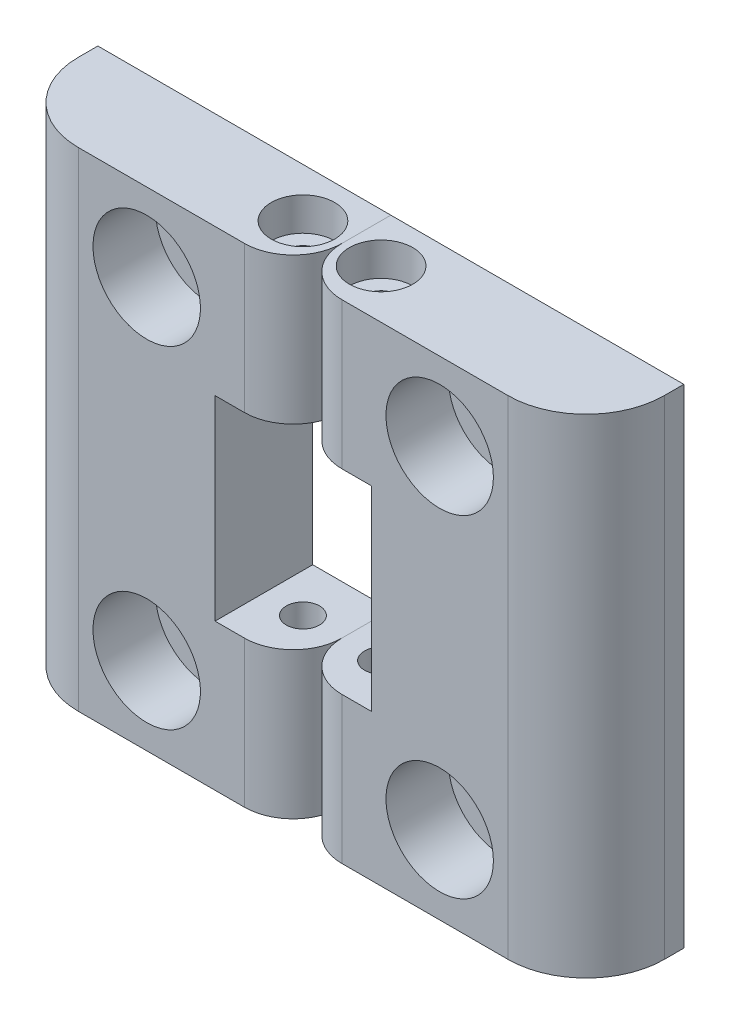
SolidWorks part; units mm, degrees
ref_plane "Přední rovina" through (0, 0, 0) normal (0, 0, 1) x (1, 0, 0)
ref_plane "Horní rovina" through (0, 0, 0) normal (0, 1, 0) x (1, 0, 0)
ref_plane "Pravá rovina" through (0, 0, 0) normal (1, 0, 0) x (0, 0, -1)
sketch "Base sketch" plane through (0, 0, 0) normal (0, 0, 1) x (1, 0, 0)
  line L0 (-15, 10) -> (-7, 10)
  line L1 (-15, 25) -> (15, 25)
  line L2 (-15, 25) -> (-15, -25)
  line L3 (-15, -25) -> (15, -25)
  line L4 (15, 25) -> (15, -25)
  line L5 (-15, 25) -> (15, -25) construction
  line L6 (-15, -25) -> (15, 25) construction
  line L7 (-7, 10) -> (-7, -10)
  line L8 (-7, -10) -> (-15, -10)
  point P0 (0, 0)
  dimension "D1" = 50
  dimension "D2" = 30
  dimension "D3" = 15
  dimension "D4" = 15
  dimension "D5" = 8
extrude "Base" add sketch "Base sketch" along normal blind 10 contours L7 L8 L2 L3 L4 L1 L0
sketch "Mount holes sketch" plane through (0, 0, 10) normal (0, 0, 1) x (1, 0, 0)
  line L0 (0, 25) -> (0, -25)
  line L1 (-15, 25) -> (15, 25) construction
  line L2 (-15, -25) -> (15, -25) construction
  point P6 (0, 17)
  point P7 (0, -17)
  dimension "D1" = 8
  dimension "D2" = 8
hole_wizard "Mount holes" positions "Skica3" profile "Skica4" counterbore size "M6" standard "DIN" end condition through all
sketch "Skica3" plane through (0, 0, 10) normal (0, 0, 1) x (1, 0, 0)
  point P0 (0, 17)
  point P3 (0, -17)
sketch "Skica4" plane through (0, 17, 10) normal (1, 0, 0) x (0, -1, 0)
  line L0 (0, 0) -> (0, 10)
  line L1 (0, 10) -> (3.3, 10)
  line L3 (3.3, 10) -> (3.3, 6.4)
  line L4 (3.3, 6.4) -> (5.5, 6.4)
  line L5 (5.5, 6.4) -> (5.5, 0)
  line L7 (5.5, 0) -> (0, 0)
  line L11 (0, -6.35) -> (0, 107.95) construction
  dimension "Průměr díry skrz" = 6.6
  dimension "Hloubka díry skrz" = 10
  dimension "Průměr válcového zahloubení" = 11
  dimension "Hloubka válcového zahloubení" = 6.4
sketch "Top screw sketch" plane through (0, 25, 0) normal (0, 1, 0) x (1, 0, 0)
  line L0 (-15, -5) -> (15, -5)
  line L1 (-15, -10) -> (-15, 0) construction
  line L2 (15, -10) -> (15, 0) construction
  point P6 (-11, -5)
  dimension "D1" = 4
hole_wizard "Top hinge" positions "Skica6" profile "Skica7" counterbore size "M3" standard "DIN"
sketch "Skica6" plane through (0, 25, 0) normal (0, 1, 0) x (1, 0, 0)
  point P0 (-11, -5)
sketch "Skica7" plane through (-11, 25, 5) normal (1, 0, 0) x (0, 0, 1)
  line L0 (0, 0) -> (0, 15)
  line L1 (0, 15) -> (1.7, 15)
  line L3 (1.7, 15) -> (1.7, 3.4)
  line L4 (1.7, 3.4) -> (3.25, 3.4)
  line L5 (3.25, 3.4) -> (3.25, 0)
  line L7 (3.25, 0) -> (0, 0)
  line L11 (0, -6.35) -> (0, 107.95) construction
  dimension "Průměr díry skrz" = 3.4
  dimension "Hloubka díry skrz" = 15
  dimension "Průměr válcového zahloubení" = 6.5
  dimension "Hloubka válcového zahloubení" = 3.4
sketch "Bottom screw sketch" plane through (0, -25, 0) normal (0, -1, 0) x (1, 0, 0)
  line L0 (-15, 5) -> (15, 5)
  line L1 (-15, 10) -> (-15, 0) construction
  line L2 (15, 10) -> (15, 0) construction
  point P6 (-11, 5)
  dimension "D1" = 4
hole_wizard "Bottom hinge" positions "Skica9" profile "Skica10" counterbore size "M3" standard "DIN" end condition up to next
sketch "Skica9" plane through (0, -25, 0) normal (0, -1, 0) x (-1, 0, 0)
  point P0 (11, -5)
sketch "Skica10" plane through (-11, -25, 5) normal (1, 0, 0) x (0, 0, -1)
  line L0 (0, 0) -> (0, 15)
  line L1 (0, 15) -> (1.7, 15)
  line L3 (1.7, 15) -> (1.7, 8)
  line L4 (1.7, 8) -> (1.9, 8)
  line L5 (1.9, 8) -> (1.9, 0)
  line L7 (1.9, 0) -> (0, 0)
  line L11 (0, -6.35) -> (0, 107.95) construction
  dimension "Průměr díry skrz" = 3.4
  dimension "Hloubka díry skrz" = 15
  dimension "Průměr válcového zahloubení" = 3.8
  dimension "Hloubka válcového zahloubení" = 8
sketch "profile sketch" plane through (0, 0, 0) normal (0, 0, -1) x (-1, 0, 0)
  line L0 (15, -25) -> (-15, -25) construction
  line L1 (-4, 25) -> (4, 25)
  line L2 (-4, 25) -> (-4, -25)
  line L3 (-4, -25) -> (4, -25)
  line L4 (4, 25) -> (4, -25)
  line L5 (-4, 25) -> (4, -25) construction
  line L6 (-4, -25) -> (4, 25) construction
  circle A0 centre (0, -17) radius 8
  circle A1 centre (0, 17) radius 8
  point P0 (0, 0)
  dimension "D2" = 16
  dimension "D1" = 8
extrude "Profile click" add sketch "profile sketch" along normal blind 3 contours A1 L2 A0 L4
fillet "Hinge round" radius 5 2 edges at (-15, -17.5, 10) (-15, 17.5, 10)
fillet "Zaoblit2" radius 8 1 edges at (15, 0, 10)
mirror "Mirror R" about plane through (-15, 0, 10) normal (1, 0, 0) of bodies 105
